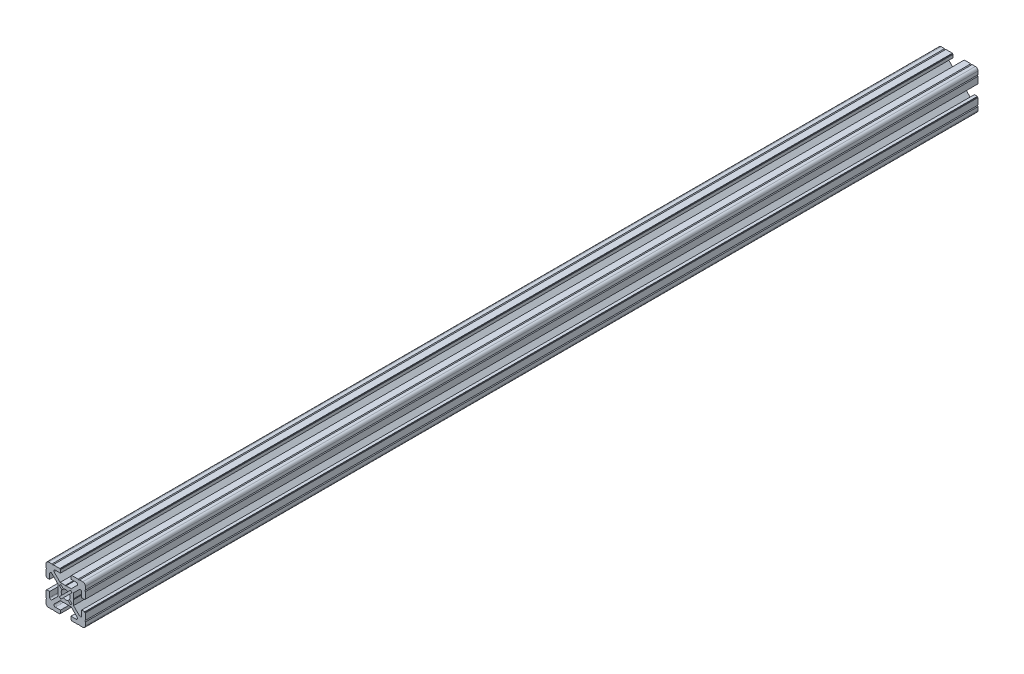
SolidWorks part; units mm, degrees
material "1060 Alloy"
ref_plane "Front" through (0, 0, 0) normal (0, 0, 1) x (1, 0, 0)
ref_plane "Top" through (0, 0, 0) normal (0, 1, 0) x (1, 0, 0)
ref_plane "Right" through (0, 0, 0) normal (1, 0, 0) x (0, 0, -1)
sketch "Sketch1" plane through (0, 0, 0) normal (0, 0, 1) x (1, 0, 0)
  line L0 (-2.9023, 1.771) -> (-4.8083, 3.677)
  line L1 (-4.8083, 3.677) -> (-3.677, 4.8083)
  line L2 (-3.677, 4.8083) -> (-1.771, 2.9023)
  line L3 (1.771, 2.9023) -> (3.677, 4.8083)
  line L4 (3.677, 4.8083) -> (4.8083, 3.677)
  line L5 (4.8083, 3.677) -> (2.9023, 1.771)
  line L6 (2.9023, -1.771) -> (4.8083, -3.677)
  line L7 (4.8083, -3.677) -> (3.677, -4.8083)
  line L8 (3.677, -4.8083) -> (1.771, -2.9023)
  line L9 (-1.771, -2.9023) -> (-3.677, -4.8083)
  line L10 (-3.677, -4.8083) -> (-4.8083, -3.677)
  line L11 (-4.8083, -3.677) -> (-2.9023, -1.771)
  line L12 (13, 15) -> (10.5, 15)
  line L13 (10.5, 15) -> (10, 14.5)
  line L14 (10, 14.5) -> (9.5, 15)
  line L15 (9.5, 15) -> (4.5, 15)
  line L16 (4.5, 15) -> (4.5, 14.5)
  line L17 (4.5, 14.5) -> (4, 14.5)
  line L18 (4, 14.5) -> (4, 12.2)
  line L19 (4, 12.2) -> (8, 12.2)
  line L20 (8.7071, 10.4929) -> (4.2142, 6)
  line L21 (4.2142, 6) -> (0.3125, 6)
  line L22 (0.3125, 6) -> (0, 5.7)
  line L23 (0, 5.7) -> (-0.3125, 6)
  line L24 (-0.3125, 6) -> (-4.2142, 6)
  line L25 (-4.2142, 6) -> (-8.7071, 10.4929)
  line L26 (-8, 12.2) -> (-4, 12.2)
  line L27 (-4, 12.2) -> (-4, 14.5)
  line L28 (-4, 14.5) -> (-4.5, 14.5)
  line L29 (-4.5, 14.5) -> (-4.5, 15)
  line L30 (-4.5, 15) -> (-9.5, 15)
  line L31 (-9.5, 15) -> (-10, 14.5)
  line L32 (-10, 14.5) -> (-10.5, 15)
  line L33 (-10.5, 15) -> (-13, 15)
  line L34 (-15, 13) -> (-15, 10.5)
  line L35 (-15, 10.5) -> (-14.5, 10)
  line L36 (-14.5, 10) -> (-15, 9.5)
  line L37 (-15, 9.5) -> (-15, 4.5)
  line L38 (-15, 4.5) -> (-14.5, 4.5)
  line L39 (-14.5, 4.5) -> (-14.5, 4)
  line L40 (-14.5, 4) -> (-12.2, 4)
  line L41 (-12.2, 4) -> (-12.2, 8)
  line L42 (-10.4929, 8.7071) -> (-6, 4.2142)
  line L43 (-6, 4.2142) -> (-6, 0.3125)
  line L44 (-6, 0.3125) -> (-5.7, 0)
  line L45 (-5.7, 0) -> (-6, -0.3125)
  line L46 (-6, -0.3125) -> (-6, -4.2142)
  line L47 (-6, -4.2142) -> (-10.4929, -8.7071)
  line L48 (-12.2, -8) -> (-12.2, -4)
  line L49 (-12.2, -4) -> (-14.5, -4)
  line L50 (-14.5, -4) -> (-14.5, -4.5)
  line L51 (-14.5, -4.5) -> (-15, -4.5)
  line L52 (-15, -4.5) -> (-15, -9.5)
  line L53 (-15, -9.5) -> (-14.5, -10)
  line L54 (-14.5, -10) -> (-15, -10.5)
  line L55 (-15, -10.5) -> (-15, -13)
  line L56 (-13, -15) -> (-10.4899, -15)
  line L57 (-10.4899, -15) -> (-9.9899, -14.5)
  line L58 (-9.9899, -14.5) -> (-9.5, -15)
  line L59 (-9.5, -15) -> (-4.5, -15)
  line L60 (-4.5, -15) -> (-4.5, -14.5)
  line L61 (-4.5, -14.5) -> (-4, -14.5)
  line L62 (-4, -14.5) -> (-4, -12.2)
  line L63 (-4, -12.2) -> (-8, -12.2)
  line L64 (-8.7071, -10.4929) -> (-4.2142, -6)
  line L65 (-4.2142, -6) -> (-0.3125, -6)
  line L66 (-0.3125, -6) -> (0, -5.7)
  line L67 (0, -5.7) -> (0.3125, -6)
  line L68 (0.3125, -6) -> (4.2142, -6)
  line L69 (4.2142, -6) -> (8.7071, -10.4929)
  line L70 (8, -12.2) -> (4, -12.2)
  line L71 (4, -12.2) -> (4, -14.5)
  line L72 (4, -14.5) -> (4.5, -14.5)
  line L73 (4.5, -14.5) -> (4.5, -15)
  line L74 (4.5, -15) -> (9.5, -15)
  line L75 (9.5, -15) -> (10, -14.5)
  line L76 (10, -14.5) -> (10.5, -15)
  line L77 (10.5, -15) -> (13, -15)
  line L78 (15, -13) -> (15, -10.5)
  line L79 (15, -10.5) -> (14.5, -10)
  line L80 (14.5, -10) -> (15, -9.5)
  line L81 (15, -9.5) -> (15, -4.5)
  line L82 (15, -4.5) -> (14.5, -4.5)
  line L83 (14.5, -4.5) -> (14.5, -4)
  line L84 (14.5, -4) -> (12.2, -4)
  line L85 (12.2, -4) -> (12.2, -8)
  line L86 (10.4929, -8.7071) -> (6, -4.2142)
  line L87 (6, -4.2142) -> (6, -0.3125)
  line L88 (6, -0.3125) -> (5.7, 0)
  line L89 (5.7, 0) -> (6, 0.3125)
  line L90 (6, 0.3125) -> (6, 4.2142)
  line L91 (6, 4.2142) -> (10.4929, 8.7071)
  line L92 (12.2, 8) -> (12.2, 4)
  line L93 (12.2, 4) -> (14.5, 4)
  line L94 (14.5, 4) -> (14.5, 4.5)
  line L95 (14.5, 4.5) -> (15, 4.5)
  line L96 (15, 4.5) -> (15, 9.5)
  line L97 (15, 9.5) -> (14.5, 10)
  line L98 (14.5, 10) -> (15, 10.5)
  line L99 (15, 10.5) -> (15, 13)
  arc A0 (-1.771, 2.9023) -> (1.771, 2.9023) centre (0, 0) cw
  arc A1 (2.9023, 1.771) -> (2.9023, -1.771) centre (0, 0) cw
  arc A2 (1.771, -2.9023) -> (-1.771, -2.9023) centre (0, 0) cw
  arc A3 (-2.9023, -1.771) -> (-2.9023, 1.771) centre (0, 0) cw
  arc A4 (8, 12.2) -> (8.7071, 10.4929) centre (8, 11.2) cw
  arc A5 (-8.7071, 10.4929) -> (-8, 12.2) centre (-8, 11.2) cw
  arc A6 (-13, 15) -> (-15, 13) centre (-13, 13) ccw
  arc A7 (-12.2, 8) -> (-10.4929, 8.7071) centre (-11.2, 8) cw
  arc A8 (-10.4929, -8.7071) -> (-12.2, -8) centre (-11.2, -8) cw
  arc A9 (-15, -13) -> (-13, -15) centre (-13, -13) ccw
  arc A10 (-8, -12.2) -> (-8.7071, -10.4929) centre (-8, -11.2) cw
  arc A11 (8.7071, -10.4929) -> (8, -12.2) centre (8, -11.2) cw
  arc A12 (13, -15) -> (15, -13) centre (13, -13) ccw
  arc A13 (12.2, -8) -> (10.4929, -8.7071) centre (11.2, -8) cw
  arc A14 (10.4929, 8.7071) -> (12.2, 8) centre (11.2, 8) cw
  arc A15 (15, 13) -> (13, 15) centre (13, 13) ccw
  dimension "D3" = 3.4
  dimension "D7" = 2
  dimension "D1" = 30
  dimension "D2" = 30
  dimension "D4" = 9
  dimension "D5" = 9
  dimension "D6" = 8
  dimension "D8" = 2.8
extrude "Boss-Extrude1" add sketch "Sketch1" along normal blind 680
